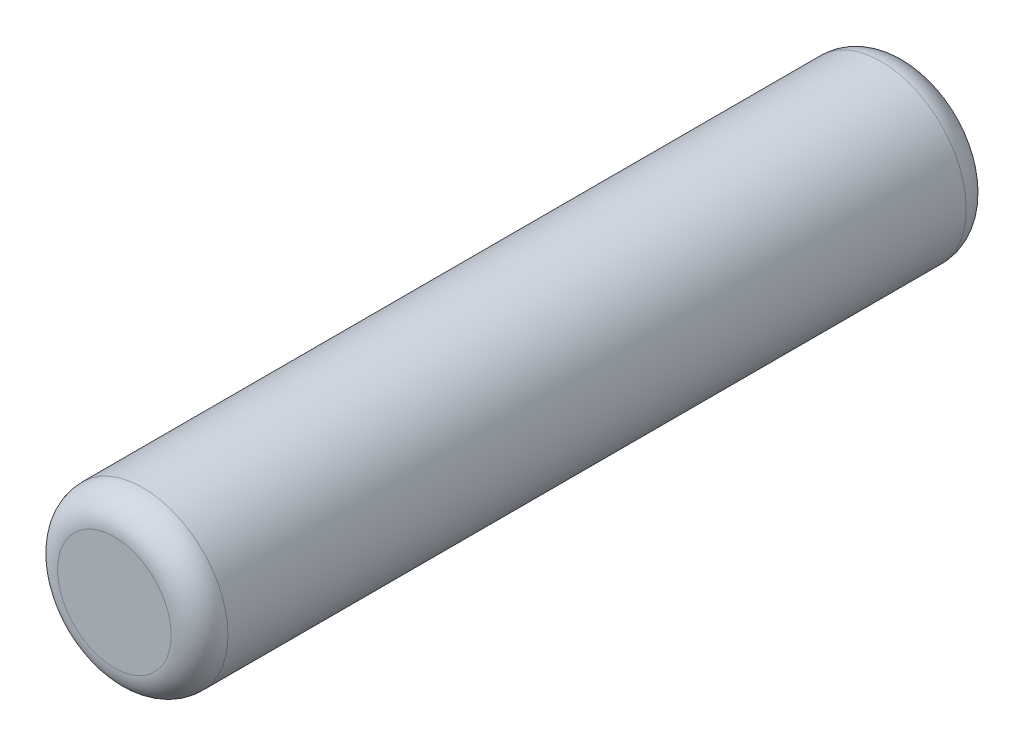
SolidWorks part; units mm, degrees
ref_plane "Płaszczyzna przednia" through (0, 0, 0) normal (0, 0, 1) x (1, 0, 0)
ref_plane "Płaszczyzna górna" through (0, 0, 0) normal (0, 1, 0) x (1, 0, 0)
ref_plane "Płaszczyzna prawa" through (0, 0, 0) normal (1, 0, 0) x (0, 0, -1)
sketch "Szkic1" plane through (0, 0, 0) normal (0, 0, 1) x (1, 0, 0)
  circle A0 centre (0, 0) radius 3
  dimension "D1" = 6
extrude "Dodanie-wyciągnięcie1" add sketch "Szkic1" along normal blind 28
fillet "Zaokrąglenie1" radius 1 2 edges at (3, 0, 0) (3, 0, 28)
